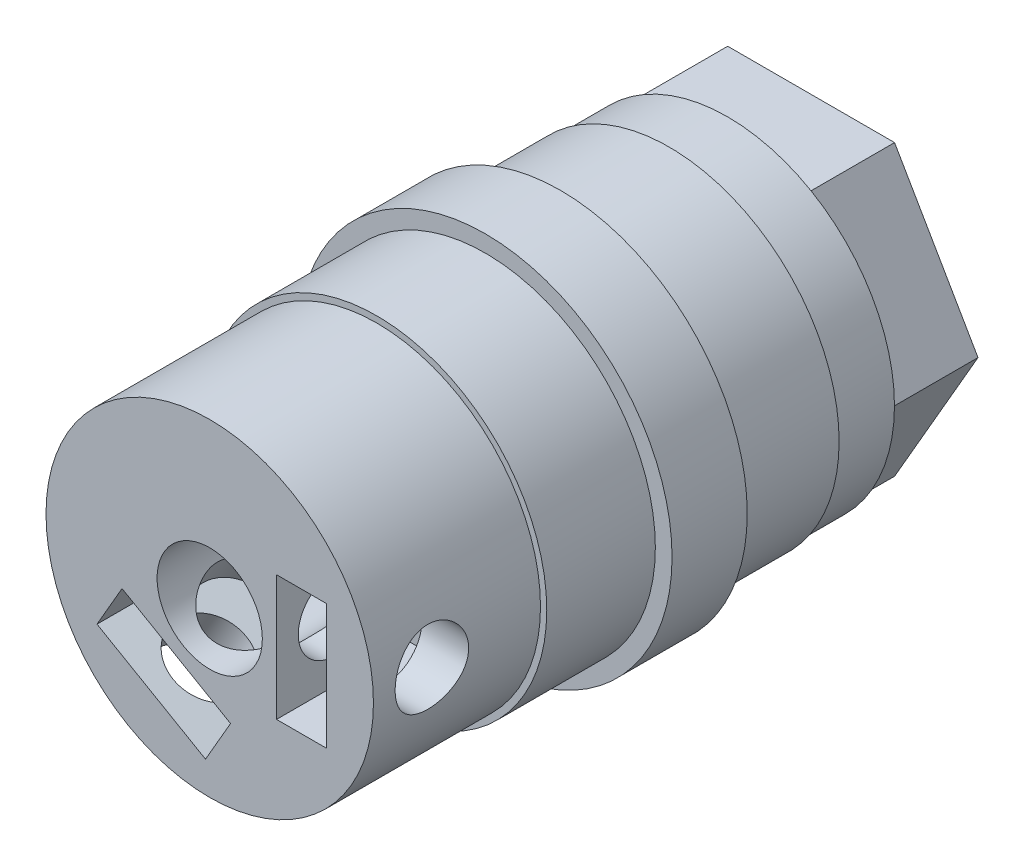
SolidWorks part; units mm, degrees
ref_plane "Спереди" through (0, 0, 0) normal (0, 0, 1) x (1, 0, 0)
ref_plane "Сверху" through (0, 0, 0) normal (0, 1, 0) x (1, 0, 0)
ref_plane "Справа" through (0, 0, 0) normal (1, 0, 0) x (0, 0, -1)
sketch "Эскиз1" plane through (0, 0, 0) normal (1, 0, 0) x (0, 0, -1)
  line L0 (0, 0) -> (0, 7.025)
  line L1 (0, 7.025) -> (16.5, 7.025)
  line L2 (16.5, 7.025) -> (16.5, 8.025)
  line L3 (16.5, 8.025) -> (21, 8.025)
  line L4 (21, 8.025) -> (21, 7.025)
  line L5 (21, 7.025) -> (31, 7.025)
  line L6 (31, 7.025) -> (31, -1.4)
  line L7 (31, -1.4) -> (14.5, -1.4)
  line L8 (0, 0) -> (14.5, 0)
  line L9 (14.5, 0) -> (14.5, -1.4)
  line L10 (0, -3.15) -> (38.6687, -3.15) construction
  line L11 (0, -3.15) -> (0, 0) construction
  line L12 (14.5, -1.4) -> (14.5, -3.15) construction
  dimension "D1" = 4.5
  dimension "D2" = 16.5
  dimension "D3" = 10
  dimension "D4" = 1
  dimension "D5" = 1.75
  dimension "D6" = 14.5
  dimension "D7" = 10.175
  dimension "D8" = 3.15
  dimension "D9" = 1.4
revolve "тело" add sketch "Эскиз1" angle 360 about L10
sketch "Эскиз2" plane through (0, 0, -31) normal (0, 0, -1) x (-1, 0, 0)
  line L1 (-7, -10.15) -> (7, -10.15) construction
  line L2 (-7, -10.15) -> (-7, 3.85) construction
  line L3 (-7, 3.85) -> (7, 3.85) construction
  line L4 (7, -10.15) -> (7, 3.85) construction
  line L5 (-7, -10.15) -> (7, 3.85) construction
  line L6 (-7, 3.85) -> (7, -10.15) construction
  line L7 (4.9941, 5.5) -> (-4.9941, 5.5)
  line L8 (-4.9941, 5.5) -> (-9.9882, -3.15)
  line L9 (-9.9882, -3.15) -> (-4.9941, -11.8)
  line L10 (-4.9941, -11.8) -> (4.9941, -11.8)
  line L11 (4.9941, -11.8) -> (9.9882, -3.15)
  line L12 (9.9882, -3.15) -> (4.9941, 5.5)
  circle A0 centre (0, -3.15) radius 1.75
  circle A1 centre (0, -3.15) radius 1.75 construction
  circle A2 centre (0, -3.15) radius 8.65 construction
  point P0 (0, -3.15)
  dimension "D1" = 14
  dimension "D2" = 17.3
extrude "шестигранник" add sketch "Эскиз2" along normal blind 5
fillet "Скругление1" radius 1 1 edges at (3.15, -3.15, -14.5)
sketch "Эскиз9" plane through (0, 0, 0) normal (0, 0, 1) x (1, 0, 0)
  line L0 (0, -3.15) -> (10.175, -3.15) construction
  line L1 (7, 0.6) -> (4, 0.6)
  line L2 (7, 0.6) -> (7, -6.9)
  line L3 (7, -6.9) -> (4, -6.9)
  line L4 (4, 0.6) -> (4, -6.9)
  line L5 (7, 0.6) -> (4, -6.9) construction
  line L6 (7, -6.9) -> (4, 0.6) construction
  line L7 (-6.7476, -7.3372) -> (-5.2476, -4.7391)
  line L8 (-0.2524, -11.0872) -> (-6.7476, -7.3372)
  line L9 (1.2476, -8.4891) -> (-5.2476, -4.7391)
  line L10 (-0.2524, -11.0872) -> (1.2476, -8.4891)
  line L11 (-6.7476, -7.3372) -> (1.2476, -8.4891) construction
  line L12 (-0.2524, -11.0872) -> (-5.2476, -4.7391) construction
  line L13 (0, -3.15) -> (-5.0875, -11.9618) construction
  circle A1 centre (0, -3.15) radius 10.175 construction
  point P0 (5.5, -3.15)
  point P19 (0, -3.15)
  dimension "D1" = 7.5
  dimension "D2" = 3
  dimension "D3" = 5.5
  dimension "D5" = 120
  dimension "D6" = 4
  dimension "D4" = 2
extrude "пазы для гаек" cut sketch "Эскиз9" against normal blind 8
sketch "Эскиз12" plane through (-3.364, -5.8266, 0) normal (-0.5, -0.866, 0) x (0.866, -0.5, 0)
  line L0 (1.575, -3.5) -> (1.575, 0) construction
  line L1 (5.325, 0) -> (-2.175, 0) construction
  line L3 (-1.925, -7) -> (5.075, 0) construction
  line L4 (-1.925, 0) -> (5.075, 0) construction
  line L5 (-1.925, 0) -> (-1.925, -7) construction
  line L6 (-1.925, -7) -> (5.075, -7) construction
  line L7 (5.075, 0) -> (5.075, -7) construction
  circle A0 centre (1.575, -3.5) radius 2.2
  point P9 (1.575, 0)
  dimension "D1" = 7
  dimension "D2" = 4.4
extrude "отверстие чтоб прикрутить 2" cut sketch "Эскиз12" against normal blind 5 and the other way blind 10
sketch "Эскиз15" plane through (0, 0, 0) normal (0, 0, 1) x (1, 0, 0)
  circle A0 centre (0, -3.15) radius 10.175
  circle A1 centre (0, -3.15) radius 10.175 construction
  circle A2 centre (0, -3.15) radius 9.8
  dimension "D1" = 19.6
  dimension "D2" = 20.35
extrude "срез под вращение вала 1" cut sketch "Эскиз15" against normal blind 10
sketch "Эскиз16" plane through (0, 0, 0) normal (1, 0, 0) x (0, 0, -1)
  line L0 (0, -3.15) -> (3.5, -3.15) construction
  line L1 (0, 6.65) -> (0, -12.95) construction
  line L2 (0, -6.65) -> (7, 0.35) construction
  line L3 (0, -6.65) -> (7, -6.65) construction
  line L4 (0, -6.65) -> (0, 0.35) construction
  line L5 (0, 0.35) -> (7, 0.35) construction
  line L6 (7, -6.65) -> (7, 0.35) construction
  circle A0 centre (3.5, -3.15) radius 2.2
  point P5 (0, -3.15)
  dimension "D1" = 4.4
  dimension "D2" = 7
extrude "отверстие чтоб прикрутить 1" cut sketch "Эскиз16" along normal through all
sketch "Эскиз18" plane through (0, 0, -31) normal (0, 0, -1) x (-1, 0, 0)
  circle A0 centre (0, -3.15) radius 10.175
  circle A1 centre (0, -3.15) radius 10.175 construction
  circle A2 centre (0, -3.15) radius 9.9882
extrude "срез под вращение вала 2" cut sketch "Эскиз18" against normal blind 3.5
